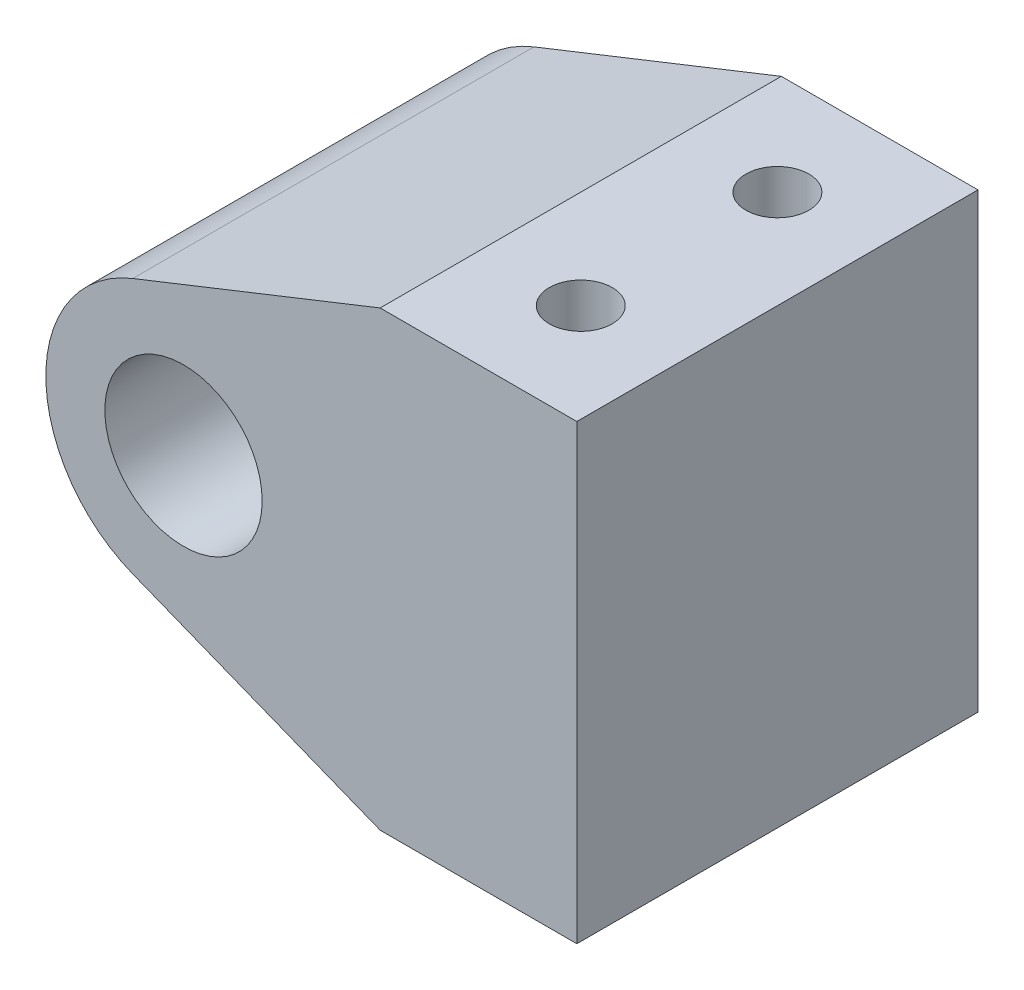
SolidWorks part; units mm, degrees
ref_plane "Front Plane" through (0, 0, 0) normal (0, 0, 1) x (1, 0, 0)
ref_plane "Top Plane" through (0, 0, 0) normal (0, 1, 0) x (1, 0, 0)
ref_plane "Right Plane" through (0, 0, 0) normal (1, 0, 0) x (0, 0, -1)
sketch "Sketch1" plane through (0, 0, 0) normal (0, 0, 1) x (1, 0, 0)
  line L0 (-10, 23) -> (0, 0) construction
  line L1 (0, 0) -> (-10, 0)
  line L2 (0, 0) -> (0, 23)
  line L3 (0, 23) -> (-10, 23)
  line L5 (-20, 11.5) -> (-5, 11.5) construction
  line L6 (-22.5822, 18.0063) -> (-10, 23)
  line L7 (-22.5822, 4.9937) -> (-10, 0)
  arc A0 (-22.5822, 18.0063) -> (-22.5822, 4.9937) centre (-20, 11.5) ccw
  circle A1 centre (-20, 11.5) radius 4
  point P10 (-5, 11.5)
  dimension "D1" = 14
  dimension "D2" = 8
  dimension "D3" = 10
  dimension "D4" = 23
  dimension "D5" = 15
  dimension "D6" = 10
extrude "Boss-Extrude1" add sketch "Sketch1" along normal blind 20.4
sketch "Sketch2" plane through (0, 23, 0) normal (0, 1, 0) x (1, 0, 0)
  line L0 (-5, 0) -> (-5, -20.4) construction
  line L1 (0, 0) -> (-10, 0) construction
  line L2 (0, -20.4) -> (-10, -20.4) construction
  circle A0 centre (-5, -5.2) radius 1.6
  circle A1 centre (-5, -15.2) radius 1.6
  dimension "D1" = 3.2
  dimension "D2" = 5.2
  dimension "D3" = 5.2
extrude "Cut-Extrude1" cut sketch "Sketch2" against normal through all
